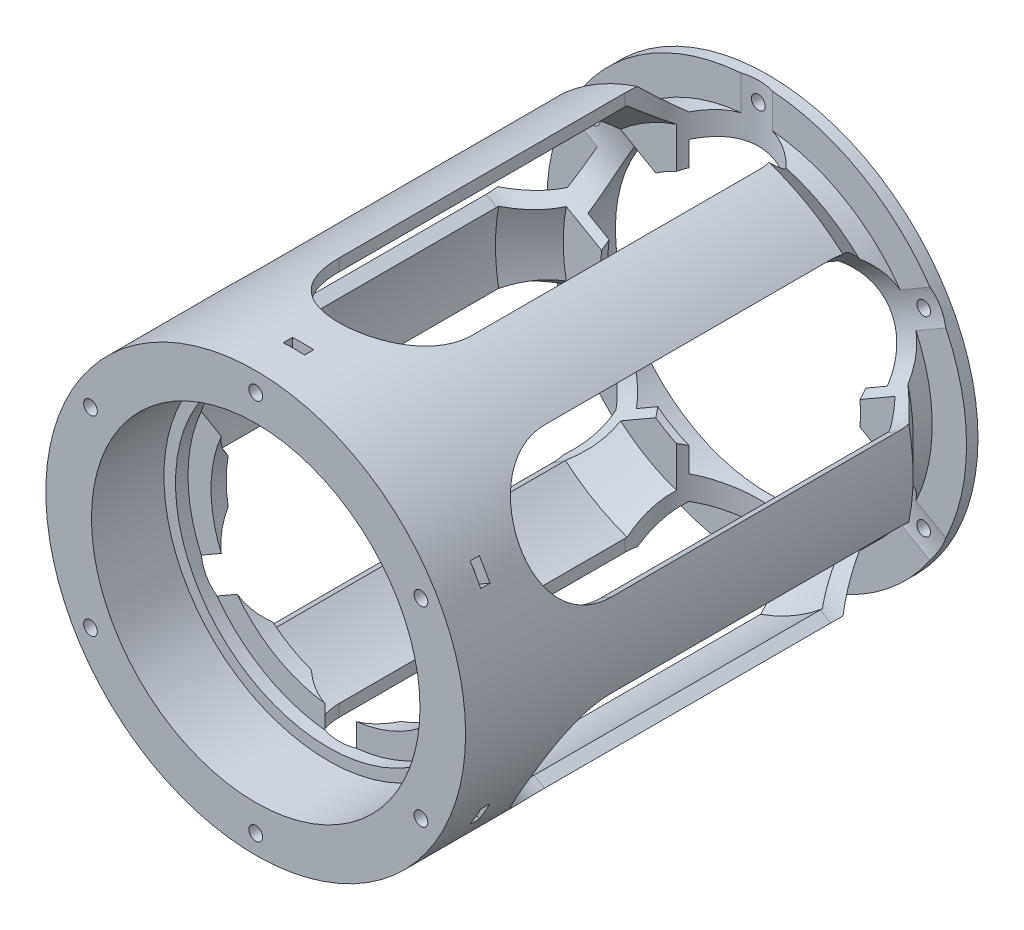
SolidWorks part; units mm, degrees
ref_plane "Front Plane" through (0, 0, 0) normal (0, 0, 1) x (1, 0, 0)
ref_plane "Top Plane" through (0, 0, 0) normal (0, 1, 0) x (1, 0, 0)
ref_plane "Right Plane" through (0, 0, 0) normal (1, 0, 0) x (0, 0, -1)
sketch "Sketch2" plane through (0, 0, 0) normal (0, 1, 0) x (1, 0, 0)
  line L0 (0, -164.1175) -> (0, 109.4658) construction
  line L1 (-106.4732, 0) -> (104.2682, 0) construction
  line L2 (55, 0) -> (40.025, 0)
  line L3 (40.025, 0) -> (40.025, -8)
  line L7 (40.025, -112) -> (40.025, -115.28)
  line L8 (40.025, -115.28) -> (43.05, -115.28)
  line L9 (43.05, -115.28) -> (43.05, -134.28)
  line L10 (43.05, -134.28) -> (55, -134.28)
  line L11 (55, -134.28) -> (55, -111)
  line L15 (55, -3) -> (55, 0)
  line L16 (40.025, -112) -> (34, -112)
  line L17 (34, -112) -> (34, -108)
  line L18 (34, -8) -> (40.025, -8)
  line L23 (34, -9.8) -> (34, -8)
  line L24 (55, -3) -> (46, -3)
  line L25 (46, -3) -> (46, -8)
  line L26 (46, -8) -> (55, -17)
  line L27 (55, -17) -> (55, -57)
  line L30 (34, -9.8) -> (43.9026, -9.8)
  line L31 (43.9026, -9.8) -> (52, -19.466)
  line L32 (52, -19.466) -> (52, -55.4489)
  line L34 (-85.1535, -108) -> (76.2276, -108) construction
  line L35 (55, -57) -> (55, -111)
  line L36 (52, -55.4489) -> (52, -106)
  line L37 (50, -108) -> (34, -108)
  line L38 (52, -106) -> (50, -108)
  point P27 (52, -108)
  dimension "D2" = 68
  dimension "D3" = 40.025
  dimension "D4" = 8
  dimension "D5" = 3.28
  dimension "D6" = 55
  dimension "D7" = 19
  dimension "D8" = 43.05
  dimension "D9" = 3
  dimension "D10" = 40.025
  dimension "D11" = 5
  dimension "D12" = 104
  dimension "D13" = 55
  dimension "D15" = 46
  dimension "D16" = 1.8
  dimension "D18" = 55
  dimension "D19" = 112
  dimension "D20" = 40
  dimension "D21" = 3
  dimension "D23" = 100
revolve "Revolve1" add sketch "Sketch2" angle 360 about L0
sketch "Sketch3" plane through (0, 0, 134.28) normal (0, 0, 1) x (1, 0, 0)
  line L0 (0, 57.5768) -> (0, -57.0977) construction
  circle A0 centre (0, 50) radius 1.8
  circle A1 centre (43.3013, 25) radius 1.8
  circle A2 centre (43.3013, -25) radius 1.8
  circle A3 centre (0, -50) radius 1.8
  circle A4 centre (-43.3013, -25) radius 1.8
  circle A5 centre (-43.3013, 25) radius 1.8
  point P17 (0, 0)
  dimension "D1" = 3.6
  dimension "D2" = 50
  dimension "D3" = 6
extrude "Cut-Extrude1" cut sketch "Sketch3" against normal through all
sketch "Sketch4" plane through (0, 0, 115.28) normal (0, 0, 1) x (1, 0, 0)
  line L0 (0, 59.4934) -> (0, -58.3754) construction
  line L1 (-2.45, 44.9333) -> (-2.45, 39.9499)
  line L2 (2.45, 44.9333) -> (2.45, 39.9499)
  circle A0 centre (0, 0) radius 40.025 construction
  circle A1 centre (0, 0) radius 43.05
  arc A3 (2.45, 39.9499) -> (-2.45, 39.9499) centre (0, 0) ccw
  circle A6 centre (0, 0) radius 43.05
  circle M5 centre (0, 0) radius 43.05
  circle M6 centre (0, 0) radius 40.025
  dimension "D2" = 2.45
  dimension "D1" = 0
extrude "Boss-Extrude1" add sketch "Sketch4" along normal blind 5 contours L0 A6 L1 M6 | L0 A3 L2 M5
ref_plane "Plane1" through (0, 0, 124.28) normal (0, 0, 1) x (1, 0, 0)
sketch "Sketch5" plane through (0, 0, 124.28) normal (0, 0, 1) x (1, 0, 0)
  line L0 (0, 71.302) -> (0, -65.8547) construction
  line L1 (-25.8624, 50) -> (32.4005, 50) construction
  line L2 (-2.8, 58.331) -> (-2.8, 47.2)
  line L3 (-2.8, 47.2) -> (2.8, 47.2)
  line L4 (2.8, 47.2) -> (2.8, 58.331)
  line L5 (2.8, 58.331) -> (-2.8, 58.331)
  line L6 (51.9161, 26.7406) -> (49.1161, 31.5904)
  line L7 (49.1161, 31.5904) -> (39.4764, 26.0249)
  line L8 (39.4764, 26.0249) -> (42.2764, 21.1751)
  line L9 (42.2764, 21.1751) -> (51.9161, 26.7406)
  line L10 (49.1161, -31.5904) -> (51.9161, -26.7406)
  line L11 (51.9161, -26.7406) -> (42.2764, -21.1751)
  line L12 (42.2764, -21.1751) -> (39.4764, -26.0249)
  line L13 (39.4764, -26.0249) -> (49.1161, -31.5904)
  line L14 (-2.8, -58.331) -> (2.8, -58.331)
  line L15 (2.8, -58.331) -> (2.8, -47.2)
  line L16 (2.8, -47.2) -> (-2.8, -47.2)
  line L17 (-2.8, -47.2) -> (-2.8, -58.331)
  line L18 (-51.9161, -26.7406) -> (-49.1161, -31.5904)
  line L19 (-49.1161, -31.5904) -> (-39.4764, -26.0249)
  line L20 (-39.4764, -26.0249) -> (-42.2764, -21.1751)
  line L21 (-42.2764, -21.1751) -> (-51.9161, -26.7406)
  line L22 (-49.1161, 31.5904) -> (-51.9161, 26.7406)
  line L23 (-51.9161, 26.7406) -> (-42.2764, 21.1751)
  line L24 (-42.2764, 21.1751) -> (-39.4764, 26.0249)
  line L25 (-39.4764, 26.0249) -> (-49.1161, 31.5904)
  point P33 (0, 0)
  dimension "D1" = 2.8
  dimension "D2" = 5.6
  dimension "D3" = 2.8
  dimension "D4" = 6
extrude "Cut-Extrude2" cut sketch "Sketch5" against normal blind 2.4
sketch "Sketch6" plane through (0, 0, 0) normal (0, 1, 0) x (1, 0, 0)
  line L0 (0, 38.0695) -> (0, -150.3703) construction
  line L1 (-17.5, -20) -> (-17.5, -95)
  line L2 (17.5, -20) -> (17.5, -95)
  arc A0 (17.5, -20) -> (-17.5, -20) centre (0, -20) ccw
  arc A1 (-17.5, -95) -> (17.5, -95) centre (0, -95) ccw
  dimension "D1" = 35
  dimension "D3" = 35
  dimension "D4" = 75
  dimension "D2" = 20
extrude "Cut-Extrude3" cut sketch "Sketch6" against normal through all both and the other way through all
pattern_circular "CirPattern1" count 3 over 360 about axis through (0, 0, 0) along (0, 0, 1) of "Cut-Extrude3"
